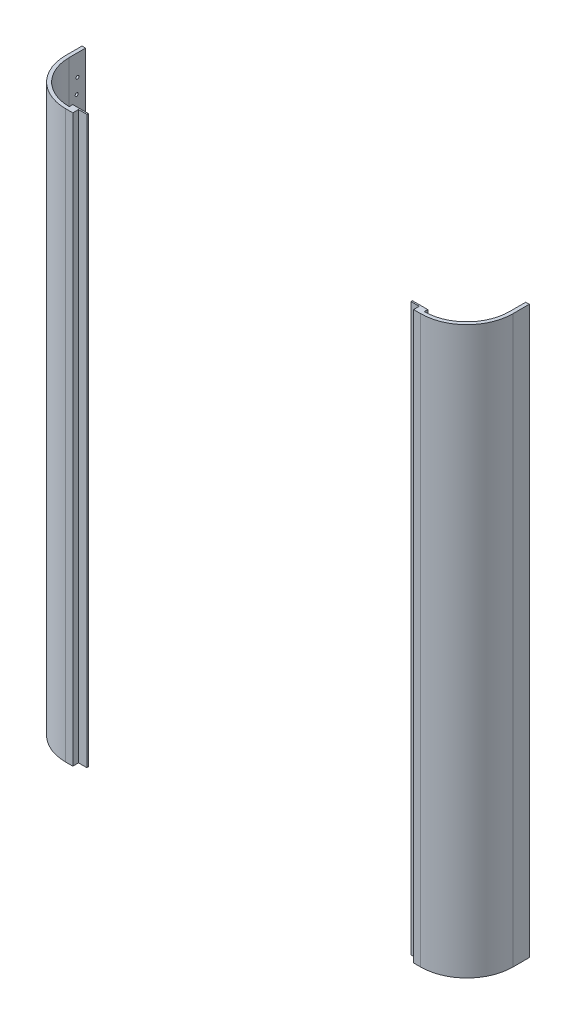
SolidWorks part; units mm, degrees
material "201 退火不锈钢 (SS)"
ref_plane "前视基准面" through (0, 0, 0) normal (0, 0, 1) x (1, 0, 0)
ref_plane "上视基准面" through (0, 0, 0) normal (0, 1, 0) x (1, 0, 0)
ref_plane "右视基准面" through (0, 0, 0) normal (1, 0, 0) x (0, 0, -1)
other "Configuration Table"
sketch "草图2" plane through (0, 0, 0) normal (0, 1, 0) x (1, 0, 0)
  line L0 (-377.2591, 276.6629) -> (-377.2591, -302.8128) construction
  line L1 (-377.2591, -302.8128) -> (320.0145, -302.8128) construction
  line L2 (320.0145, 276.6629) -> (320.0145, -302.8128) construction
  line L3 (-28.6223, 276.6629) -> (-28.6223, -302.8128) construction
  line L11 (-278.6223, -303.6706) -> (-278.6223, -308.6706)
  line L12 (-256.8547, -303.6706) -> (-278.6223, -303.6706)
  line L13 (-256.8547, -305.6706) -> (-256.8547, -303.6706)
  line L14 (-268.6223, -305.6706) -> (-256.8547, -305.6706)
  line L15 (-268.6223, -308.6706) -> (-268.6223, -305.6706)
  line L16 (-268.6223, -313.6706) -> (-268.6223, -308.6706)
  line L17 (-278.6223, -313.6706) -> (-268.6223, -313.6706)
  line L20 (281.3777, -248.6706) -> (281.3777, -225.6706)
  line L26 (-343.6223, -248.6706) -> (-343.6223, -225.6706)
  line L27 (-343.6223, -225.6706) -> (-338.6223, -225.6706)
  line L28 (-338.6223, -248.6706) -> (-338.6223, -225.6706)
  line L29 (286.3777, -225.6706) -> (281.3777, -225.6706)
  line L30 (286.3777, -248.6706) -> (286.3777, -225.6706)
  line L31 (221.3777, -313.6706) -> (211.3777, -313.6706)
  line L32 (211.3777, -313.6706) -> (211.3777, -308.6706)
  line L33 (211.3777, -308.6706) -> (211.3777, -305.6706)
  line L34 (211.3777, -305.6706) -> (199.6101, -305.6706)
  line L35 (199.6101, -305.6706) -> (199.6101, -303.6706)
  line L36 (199.6101, -303.6706) -> (221.3777, -303.6706)
  line L37 (221.3777, -303.6706) -> (221.3777, -308.6706)
  arc A2 (-278.6223, -313.6706) -> (-343.6223, -248.6706) centre (-278.6223, -248.6706) cw
  arc A3 (-278.6223, -308.6706) -> (-338.6223, -248.6706) centre (-278.6223, -248.6706) cw
  arc A4 (221.3777, -308.6706) -> (281.3777, -248.6706) centre (221.3777, -248.6706) ccw
  arc A5 (221.3777, -313.6706) -> (286.3777, -248.6706) centre (221.3777, -248.6706) ccw
  dimension "D3" = 60
  dimension "D4" = 8
  dimension "D1" = 500
  dimension "D2" = 23
  dimension "D5" = 2
  dimension "D6" = 10
  dimension "D7" = 5
extrude "凸台-拉伸1" add sketch "草图2" along normal blind 797
sketch "草图3" plane through (-338.6223, 0, 0) normal (1, 0, 0) x (0, 0, -1)
  line L0 (-248.6706, 797) -> (-225.6706, 797) construction
  line L1 (-225.6706, 405.5) -> (-176.7668, 405.5) construction
  line L2 (-225.6706, 797) -> (-225.6706, 0) construction
  circle A0 centre (-237.1706, 767) radius 2.15
  circle A1 centre (-238.1706, 746.5) radius 2.15
  circle A2 centre (-237.1706, 726) radius 2.15
  circle A3 centre (-237.1706, 85) radius 2.15
  circle A4 centre (-238.1706, 64.5) radius 2.15
  circle A5 centre (-237.1706, 44) radius 2.15
  circle A6 centre (-237.1706, 426) radius 2.15
  circle A7 centre (-238.1706, 405.5) radius 2.15
  circle A8 centre (-237.1706, 385) radius 2.15
  dimension "D1" = 4.3
  dimension "D2" = 4.3
  dimension "D3" = 4.3
  dimension "D9" = 4.3
  dimension "D10" = 4.3
  dimension "D11" = 4.3
  dimension "D4" = 20.5
  dimension "D5" = 11.5
  dimension "D6" = 20.5
  dimension "D7" = 12.5
  dimension "D8" = 30
  dimension "D12" = 20.5
  dimension "D13" = 20.5
  dimension "D14" = 11.5
  dimension "D15" = 12.5
  dimension "D16" = 300
  dimension "D17" = 300
extrude "切除-拉伸1" cut sketch "草图3" along normal blind 20 and the other way through all
